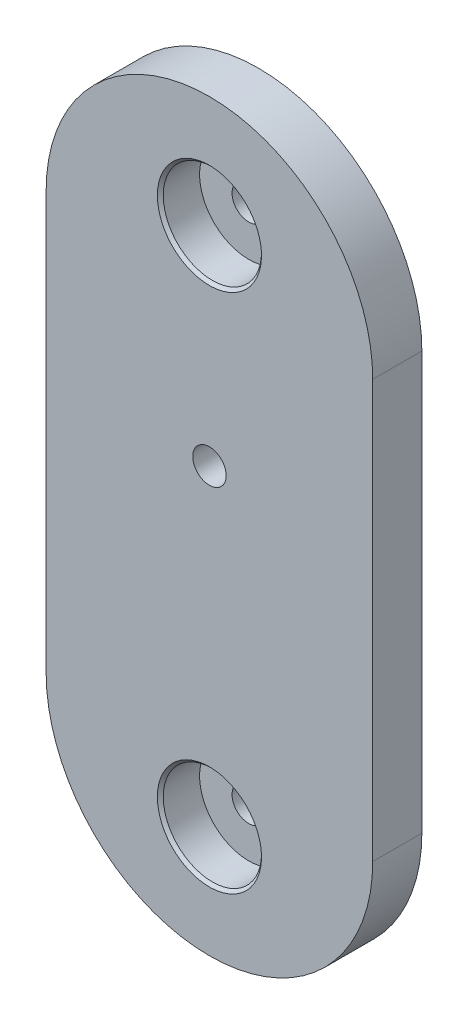
SolidWorks part; units mm, degrees
material "1060 Alloy"
ref_plane "Front Plane" through (0, 0, 0) normal (0, 0, 1) x (1, 0, 0)
ref_plane "Top Plane" through (0, 0, 0) normal (0, 1, 0) x (1, 0, 0)
ref_plane "Right Plane" through (0, 0, 0) normal (1, 0, 0) x (0, 0, -1)
sketch "Sketch1" plane through (0, 0, 0) normal (0, 0, 1) x (1, 0, 0)
  line L0 (-16.6225, -21.2525) -> (-16.6225, 21.2525)
  line L1 (-16.6225, 21.2525) -> (16.6225, 21.2525) construction
  line L2 (16.6225, 21.2525) -> (16.6225, -21.2525)
  line L3 (-16.6225, -21.2525) -> (16.6225, -21.2525) construction
  line L4 (0, 37.875) -> (0, -37.875) construction
  line L5 (0, 26.5125) -> (0, -26.5125) construction
  arc A0 (-16.6225, 21.2525) -> (16.6225, 21.2525) centre (0, 21.2525) cw
  arc A1 (16.6225, -21.2525) -> (-16.6225, -21.2525) centre (0, -21.2525) cw
  circle A4 centre (0, 26.5125) radius 1.7
  circle A5 centre (0, -26.5125) radius 1.7
  point P6 (0, 0)
  point P14 (0, 0)
  dimension "D3" = 3.4
  dimension "D1" = 33.245
  dimension "D2" = 75.75
  dimension "D4" = 53.025
extrude "Boss-Extrude1" add sketch "Sketch1" along normal blind 5
sketch "Sketch3" plane through (0, 0, 5) normal (0, 0, 1) x (1, 0, 0)
  line L0 (0, 26.5125) -> (0, -26.5125) construction
  circle A0 centre (0, 26.5125) radius 5
  circle A1 centre (0, -26.5125) radius 5
  point P4 (0, 0)
  dimension "D2" = 10
  dimension "D1" = 53.025
extrude "Cut-Extrude1" cut sketch "Sketch3" against normal blind 4
ref_plane "Plane1" through (0, 0, 0) normal (1, 0, 0) x (0, 0, -1)
sketch "Sketch2" plane through (0, 0, 0) normal (1, 0, 0) x (0, 0, -1)
  line L1 (-5, 31.5125) -> (-5, 21.5125) construction
  line L2 (-5, 21.5125) -> (0, 21.5125) construction
  line L3 (0, 21.2525) -> (0, -21.2525) construction
  line L5 (-2.5, 26.5125) -> (-2.5, 5.3025) construction
  line L6 (-5, 5.3025) -> (0, 5.3025)
  line L7 (-5, 21.2525) -> (-5, -21.2525) construction
  line L8 (-5, 5.3025) -> (-5, 3.6025)
  line L9 (-5, 3.6025) -> (-1.3, 3.6025)
  line L10 (-1.3, 3.6025) -> (0, 2.3025)
  line L11 (0, 2.3025) -> (0, 5.3025)
  line L12 (-13.6129, 5.3025) -> (9.2612, 5.3025) construction
  line L13 (-5, 31.5125) -> (-5, 21.5125) construction
  point P0 (-2.5, 26.5125)
  point P1 (-2.5, 21.5125)
  point P10 (-5, 26.5125)
  dimension "D1" = 21.21
  dimension "D2" = 3.4
  dimension "D3" = 6
  dimension "D4" = 45
revolve "Cut-Revolve1" cut sketch "Sketch2" angle 360 about L12
chamfer "Chamfer1" distance 0.3 angle 45 2 edges at (5, -26.5125, 5) (5, 26.5125, 5)
equation "\"L\"=0.053025"
equation "\"H\"=0.075750"
equation "\"B\"=0.033245"
equation "\"T\"=0.005000"
equation "\"D1@Sketch1\"=\"B\"*1000"
equation "\"D2@Sketch1\"=\"H\"*1000"
equation "\"D4@Sketch1\"=\"L\"*1000"
equation "\"D1@Boss-Extrude1\"=\"T\"*1000"
equation "\"bearing_hole_diameter\"=0.010000"
equation "\"spring_arm_hole_pos\"=0.021210"
equation "\"D1@Sketch2\"=\"spring_arm_hole_pos\"*1000"
equation "\"spring_arm_hole_max_diam\"=0.006000"
equation "\"spring_arm_hole_min_diam\"=0.003400"
equation "\"arm_hole_head_height\"=0.001650"
equation "\"D2@Sketch2\"=\"spring_arm_hole_min_diam\"*1000"
equation "\"D3@Sketch2\"=\"spring_arm_hole_max_diam\"*1000"
equation "\"D1@Sketch3\"=\"L\"*1000"
equation "\"D2@Sketch3\"=\"bearing_hole_diameter\"*1000"
equation "\"bearing_depth\"=0.004000"
equation "\"D1@Cut-Extrude1\"=\"bearing_depth\"*1000"
equation "\"bolt_hole_diameter\"=0.003400"
equation "\"D3@Sketch1\"=\"bolt_hole_diameter\"*1000"
